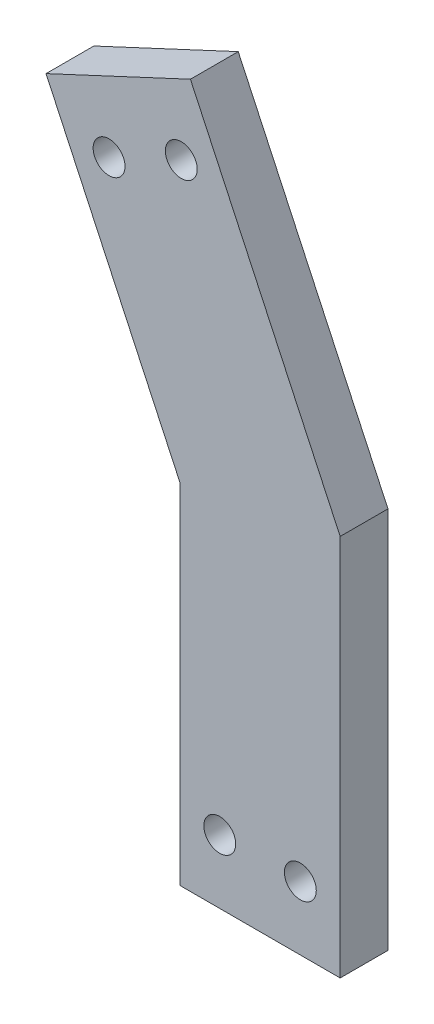
SolidWorks part; units mm, degrees
ref_plane "Ön Düzlem" through (0, 0, 0) normal (0, 0, 1) x (1, 0, 0)
ref_plane "Üst Düzlem" through (0, 0, 0) normal (0, 1, 0) x (1, 0, 0)
ref_plane "Sağ Düzlem" through (0, 0, 0) normal (1, 0, 0) x (0, 0, -1)
sketch "Çizim1" plane through (0, 0, 0) normal (0, 0, 1) x (1, 0, 0)
  line L0 (23.0761, -55.1921) -> (23.0761, 4.8079)
  line L1 (23.0761, 4.8079) -> (-0.4184, 55.1921)
  line L2 (-0.4184, 55.1921) -> (-23.0761, 44.6266)
  line L3 (-23.0761, 44.6266) -> (-2.0675, -0.4264)
  line L4 (-2.0675, -0.4264) -> (-2.0675, -55.1921)
  line L5 (-2.0675, -55.1921) -> (23.0761, -55.1921)
  line L6 (-20.1202, 38.2877) -> (2.5375, 48.8531) construction
  line L7 (2.5375, 48.8531) -> (5.078, 43.4049) construction
  line L8 (-8.7914, 43.5704) -> (-6.2508, 38.1222) construction
  line L9 (-14.4558, 40.929) -> (-11.9152, 35.4808) construction
  line L10 (-3.1269, 46.2118) -> (-0.5864, 40.7635) construction
  line L11 (-2.0675, -48.1978) -> (23.0761, -48.1978) construction
  line L12 (10.5043, -48.1978) -> (10.5043, -42.1864) construction
  line L13 (4.1825, -48.1978) -> (4.1825, -42.1864) construction
  line L14 (16.8261, -48.1978) -> (16.8261, -42.1864) construction
  circle A0 centre (-13.1855, 38.2049) radius 2.5
  circle A1 centre (-1.8567, 43.4876) radius 2.5
  circle A2 centre (4.1825, -45.1921) radius 2.5
  circle A3 centre (16.8261, -45.1921) radius 2.5
  dimension "D4" = 5
  dimension "D5" = 5
  dimension "D8" = 5
  dimension "D9" = 5
  dimension "D1" = 25
  dimension "D2" = 6.25
  dimension "D3" = 6.25
  dimension "D6" = 6.25
  dimension "D7" = 6.25
extrude "Yükseklik-Ekstrüzyon1" add sketch "Çizim1" along normal blind 7.5
